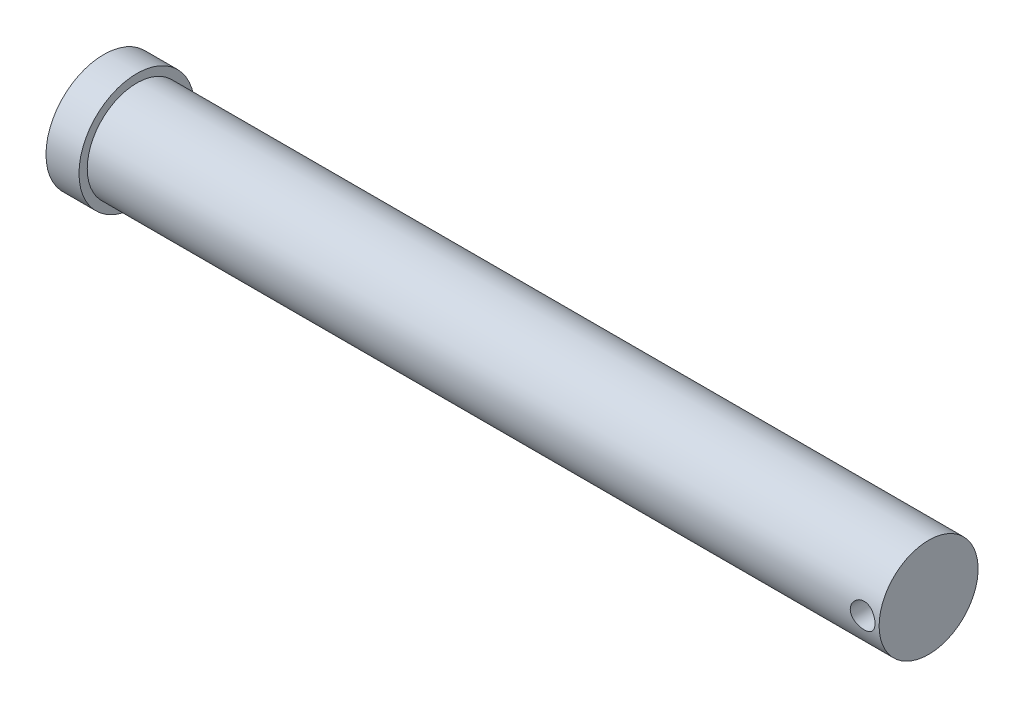
SolidWorks part; units mm, degrees
material "AISI 1020"
ref_plane "Ön Düzlem" through (0, 0, 0) normal (0, 0, 1) x (1, 0, 0)
ref_plane "Üst Düzlem" through (0, 0, 0) normal (0, 1, 0) x (1, 0, 0)
ref_plane "Sağ Düzlem" through (0, 0, 0) normal (1, 0, 0) x (0, 0, -1)
sketch "Çizim1" plane through (0, 0, 0) normal (0, 0, 1) x (1, 0, 0)
  line L0 (0, 0) -> (500, 0) construction
  line L1 (0, 0) -> (0, 35)
  line L2 (0, 35) -> (20, 35)
  line L3 (20, 35) -> (20, 30)
  line L4 (20, 30) -> (500, 30)
  line L5 (500, 30) -> (500, 0)
  line L6 (0, 0) -> (500, 0)
  dimension "D1" = 500
  dimension "D2" = 20
  dimension "D3" = 5
  dimension "D4" = 30
revolve "Döndür1" add sketch "Çizim1" angle 360 about L0
sketch "Çizim2" plane through (0, 0, 0) normal (0, 0, 1) x (1, 0, 0)
  line L0 (500, -30) -> (500, 30) construction
  circle A0 centre (490, 0) radius 7.5
  dimension "D2" = 15
  dimension "D1" = 10
extrude "Kes-Ekstrüzyon1" cut sketch "Çizim2" against normal mid plane 60
